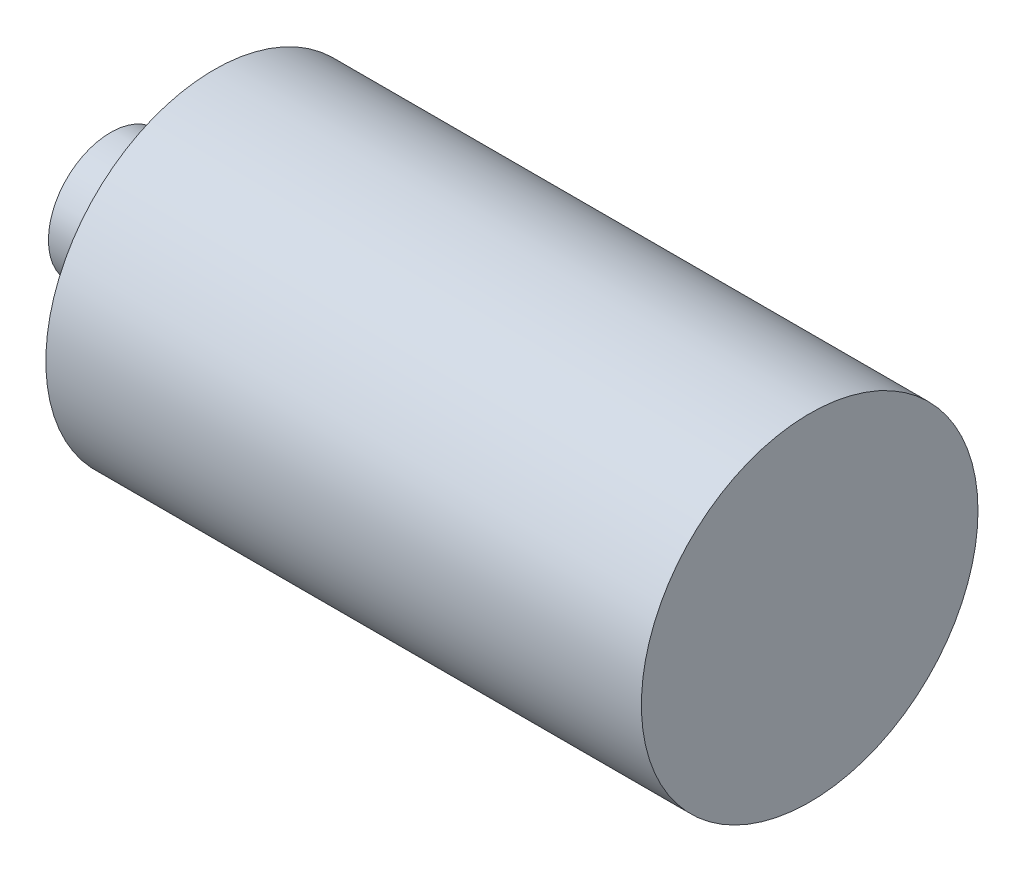
SolidWorks part; units mm, degrees
ref_plane "前视基准面" through (0, 0, 0) normal (0, 0, 1) x (1, 0, 0)
ref_plane "上视基准面" through (0, 0, 0) normal (0, 1, 0) x (1, 0, 0)
ref_plane "右视基准面" through (0, 0, 0) normal (1, 0, 0) x (0, 0, -1)
sketch "草图1" plane through (0, 0, 0) normal (1, 0, 0) x (0, 0, -1)
  circle A0 centre (0, 0) radius 3.25
  dimension "D1" = 6.5
extrude "凸台-拉伸1" add sketch "草图1" along normal blind 11.5
sketch "草图2" plane through (0, 0, 0) normal (-1, 0, 0) x (0, 0, 1)
  circle A0 centre (0, 0) radius 1.2
  dimension "D1" = 2.4
extrude "凸台-拉伸2" add sketch "草图2" along normal blind 2
